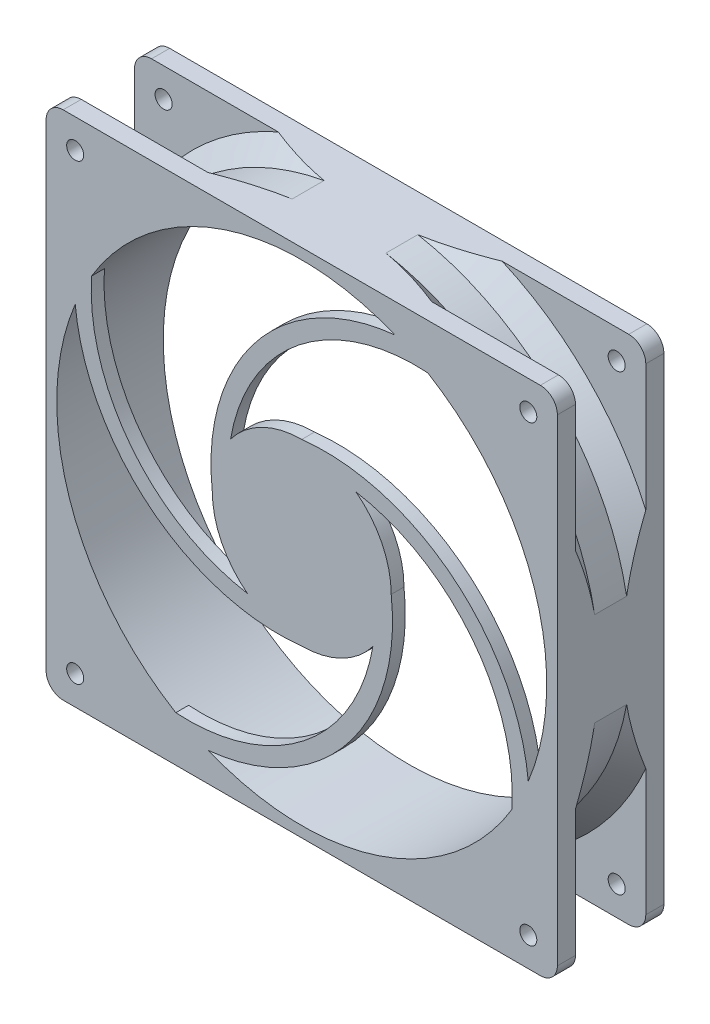
SolidWorks part; units mm, degrees
ref_plane "Front Plane" through (0, 0, 0) normal (0, 0, 1) x (1, 0, 0)
ref_plane "Top Plane" through (0, 0, 0) normal (0, 1, 0) x (1, 0, 0)
ref_plane "Right Plane" through (0, 0, 0) normal (1, 0, 0) x (0, 0, -1)
sketch "Sketch1" plane through (0, 0, 0) normal (0, 0, 1) x (1, 0, 0)
  line L0 (58, -58) -> (58, -30.4344)
  line L1 (60, -60) -> (-60, -60)
  line L2 (60, -60) -> (60, 60)
  line L3 (60, 60) -> (-60, 60)
  line L4 (-60, -60) -> (-60, 60)
  line L5 (60, -60) -> (-60, 60) construction
  line L6 (60, 60) -> (-60, -60) construction
  line L11 (58, 58) -> (30.4344, 58)
  line L12 (-58, -58) -> (-58, -30.4344)
  line L13 (58, -58) -> (30.4344, -58)
  line L14 (-30.4344, 58) -> (-58, 58)
  line L15 (58, 58) -> (-58, 58) construction
  line L16 (58, 30.4344) -> (58, 58)
  line L17 (58, -58) -> (58, 58) construction
  line L18 (-58, 30.4344) -> (-58, 58)
  line L19 (-58, -58) -> (-58, 58) construction
  line L20 (-30.4344, -58) -> (-58, -58)
  line L21 (58, -58) -> (-58, -58) construction
  circle A0 centre (0, 0) radius 57.5
  arc A1 (-30.4344, 58) -> (-58, 30.4344) centre (0, 0) ccw
  arc A2 (58, 30.4344) -> (30.4344, 58) centre (0, 0) ccw
  arc A3 (-58, -30.4344) -> (-30.4344, -58) centre (0, 0) ccw
  arc A4 (30.4344, -58) -> (58, -30.4344) centre (0, 0) ccw
  point P0 (0, 0)
  dimension "D3" = 115
  dimension "D4" = 8
  dimension "D1" = 120
  dimension "D2" = 120
  dimension "D5" = 2
extrude "Boss-Extrude1" add sketch "Sketch1" along normal blind 25 contours A1 L14 L18 | L4 L1 L2 L3 A0 L14 A1 L18 L16 A2 L11 L12 A3 L20 L13 A4 L0 | A4 L13 L0 | A3 L12 L20
fillet "Fillet1" radius 4 4 edges at (60, -60, 12.5) (60, 60, 12.5) (-60, -60, 12.5) (-60, 60, 12.5)
sketch "Sketch2" plane through (0, 0, 0) normal (0, 1, 0) x (1, 0, 0)
  line L0 (61, -8.75) -> (61, -16.25)
  line L2 (61, -16.25) -> (65.5, -20.75)
  line L3 (65.5, -20.75) -> (86, -20.75)
  line L4 (86, -20.75) -> (86, -4.25)
  line L5 (86, -4.25) -> (65.5, -4.25)
  line L6 (65.5, -4.25) -> (61, -8.75)
  line L7 (60, 0) -> (60, -25) construction
  line L8 (0, 0) -> (0, -25) construction
  line L9 (56, 0) -> (-56, 0) construction
  line L10 (56, -25) -> (-56, -25) construction
  point P4 (60, -12.5)
  point P9 (61, -12.5)
  point P11 (86, -2.7951)
  dimension "D1" = 25
  dimension "D2" = 16.5
  dimension "D3" = 4.5
  dimension "D4" = 7.5
  dimension "D5" = 1
revolve "Cut-Revolve1" cut sketch "Sketch2" angle 360 about L8
sketch "Sketch3" plane through (0, 0, 0) normal (0, 0, -1) x (-1, 0, 0)
  line L0 (-58.8284, 58.8284) -> (58.8284, -58.8284) construction
  line L1 (-58.8284, -58.8284) -> (58.8284, 58.8284) construction
  arc A0 (-56, 60) -> (-60, 56) centre (-56, 56) ccw construction
  arc A1 (56, -60) -> (60, -56) centre (56, -56) ccw construction
  arc A2 (-60, -56) -> (-56, -60) centre (-56, -56) ccw construction
  arc A3 (60, 56) -> (56, 60) centre (56, 56) ccw construction
  circle A4 centre (-53.1716, 53.1716) radius 2
  circle A5 centre (53.1716, 53.1716) radius 2
  circle A6 centre (53.1716, -53.1716) radius 2
  circle A7 centre (-53.1716, -53.1716) radius 2
  point P24 (0, 0)
  point P25 (0, 0)
  point P26 (0, 0)
  point P27 (0, 0)
  point P28 (51.9669, 51.9669)
  dimension "D1" = 4
  dimension "D2" = 8
extrude "Cut-Extrude1" cut sketch "Sketch3" against normal through all
sketch "Sketch4" plane through (0, 0, 25) normal (0, 0, 1) x (1, 0, 0)
  arc A0 (0, 21) -> (-16.6912, 12.7438) centre (0, 0) ccw
  arc A1 (-21, 0) -> (21.8868, 53.1716) centre (26.6938, 5.4129) cw
  arc A2 (-16.6912, 12.7438) -> (29.561, 49.3194) centre (26.6938, 5.4129) cw
  arc A3 (-17.0255, 0.4511) -> (22.2874, 49.1917) centre (26.6938, 5.4129) cw construction
  circle A4 centre (0, 0) radius 57.5 construction
  arc A5 (0, 21) -> (53.1716, -21.8868) centre (5.4129, -26.6938) cw
  arc A6 (12.7438, 16.6912) -> (49.3194, -29.561) centre (5.4129, -26.6938) cw
  arc A7 (21, 0) -> (-21.8868, -53.1716) centre (-26.6938, -5.4129) cw
  arc A8 (16.6912, -12.7438) -> (-29.561, -49.3194) centre (-26.6938, -5.4129) cw
  arc A9 (0, -21) -> (-53.1716, 21.8868) centre (-5.4129, 26.6938) cw
  arc A10 (-12.7438, -16.6912) -> (-49.3194, 29.561) centre (-5.4129, 26.6938) cw
  arc A11 (21, 0) -> (12.7438, 16.6912) centre (0, 0) ccw
  arc A12 (0, -21) -> (16.6912, -12.7438) centre (0, 0) ccw
  arc A13 (-49.3194, 29.561) -> (-53.1716, 21.8868) centre (0, 0) ccw
  arc A14 (29.561, 49.3194) -> (21.8868, 53.1716) centre (0, 0) ccw
  arc A15 (49.3194, -29.561) -> (53.1716, -21.8868) centre (0, 0) ccw
  arc A16 (-29.561, -49.3194) -> (-21.8868, -53.1716) centre (0, 0) ccw
  arc A17 (-21, 0) -> (-12.7438, -16.6912) centre (0, 0) ccw
  point P13 (53.1716, 53.1716)
  point P36 (0, 0)
  dimension "D1" = 42
  dimension "D2" = 4
  dimension "D3" = 48
  dimension "D4" = 4
extrude "Boss-Extrude2" add sketch "Sketch4" against normal blind 3
